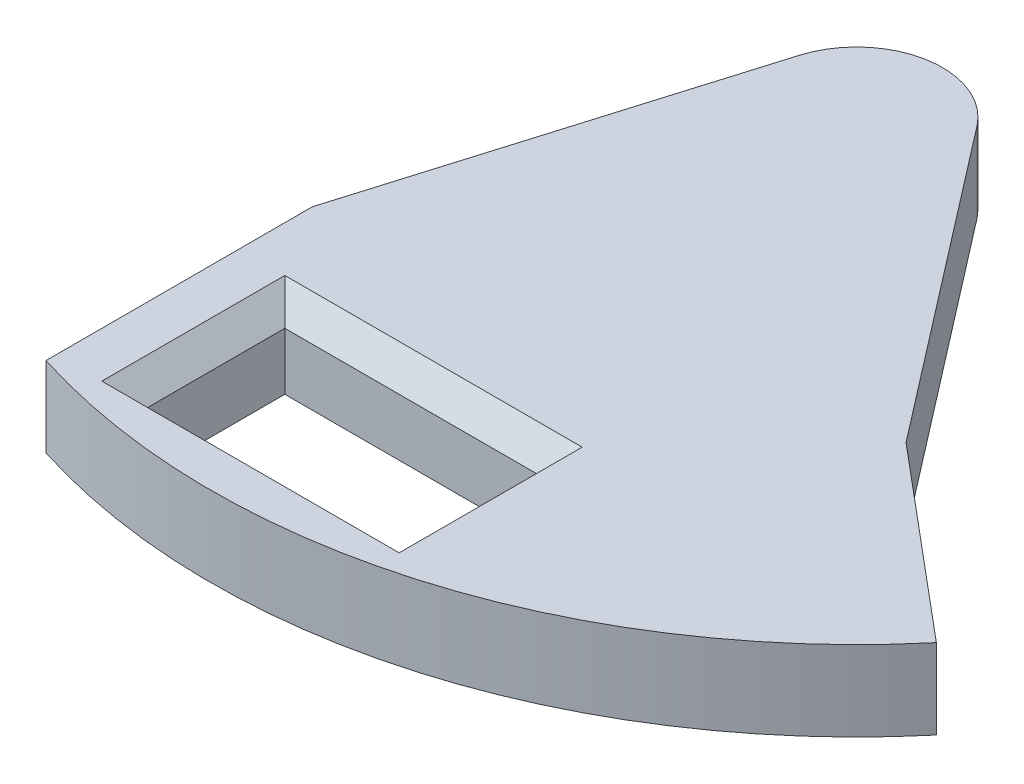
SolidWorks part; units mm, degrees
ref_plane "Front Plane" through (0, 0, 0) normal (0, 0, 1) x (1, 0, 0)
ref_plane "Top Plane" through (0, 0, 0) normal (0, 1, 0) x (1, 0, 0)
ref_plane "Right Plane" through (0, 0, 0) normal (1, 0, 0) x (0, 0, -1)
sketch "Sketch1" plane through (0, 0, 0) normal (0, 1, 0) x (1, 0, 0)
  line L0 (0, 45) -> (0, 0) construction
  line L1 (-11, 6) -> (11, 6)
  line L2 (-11, 6) -> (-11, -6)
  line L3 (-11, -6) -> (11, -6)
  line L4 (11, 6) -> (11, -6)
  line L5 (-11, 6) -> (11, -6) construction
  line L6 (-11, -6) -> (11, 6) construction
  line L11 (0, 45) -> (43.2815, 8.6825)
  line L12 (-17, 14.4059) -> (-17, -8.8818)
  line L13 (-7.1842, 47.1534) -> (-17, 14.4059)
  line L14 (5.9401, 49.5788) -> (26.8116, 22.5024)
  circle A0 centre (0, 45) radius 45 construction
  circle A1 centre (0, 45) radius 56.5
  circle A2 centre (0, 45) radius 35
  circle A3 centre (0, 45) radius 7.5
  point P0 (0, 0)
  point P5 (0, 0)
  point P11 (0, 45)
  point P18 (0, 0)
  dimension "D3" = 45
  dimension "D4" = 70
  dimension "D5" = 113
  dimension "D8" = 15
  dimension "D1" = 12
  dimension "D2" = 22
  dimension "D6" = 50
  dimension "D7" = 6
extrude "Boss-Extrude1" add sketch "Sketch1" along normal blind 7
chamfer "Chamfer1" distance 2 angle 45 4 edges at (-11, 7, 0) (0, 7, 6) (11, 7, 0) (0, 7, -6)
